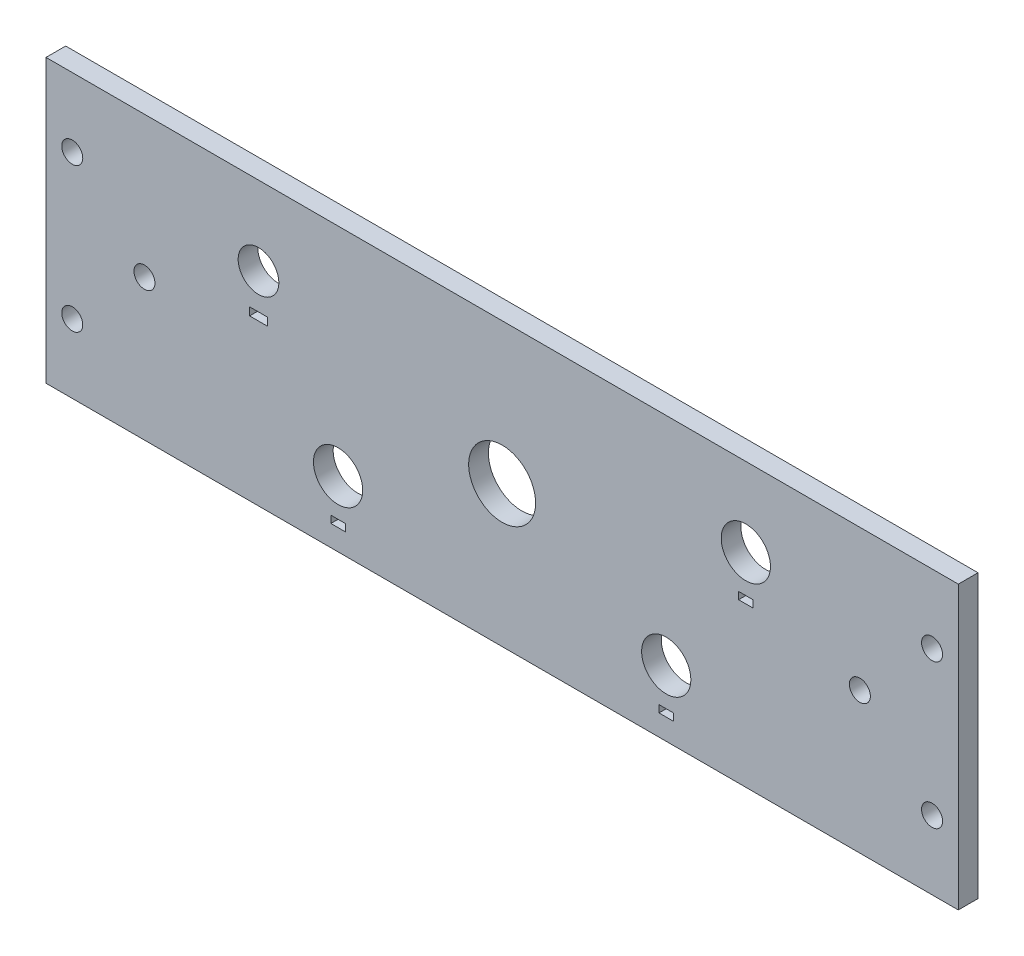
SolidWorks part; units mm, degrees
ref_plane "Front Plane" through (0, 0, 0) normal (0, 0, 1) x (1, 0, 0)
ref_plane "Top Plane" through (0, 0, 0) normal (0, 1, 0) x (1, 0, 0)
ref_plane "Right Plane" through (0, 0, 0) normal (1, 0, 0) x (0, 0, -1)
sketch "Sketch1" plane through (0, 0, 0) normal (0, 0, 1) x (1, 0, 0)
  line L0 (44.5, 10) -> (94.5, 10) construction
  line L1 (0, 0) -> (139, 0)
  line L2 (0, 0) -> (0, 43)
  line L3 (0, 43) -> (139, 43)
  line L4 (139, 0) -> (139, 43)
  line L5 (69.5, 43) -> (69.5, 0) construction
  line L12 (45.6, 3.2) -> (43.4, 4.3) construction
  line L17 (32.3756, 31) -> (32.3756, 25) construction
  line L19 (94.5, 10) -> (94.5, 0) construction
  line L20 (31.0256, 24.4) -> (33.7256, 24.4)
  line L21 (93.4, 3.2) -> (95.6, 3.2)
  line L22 (93.4, 3.2) -> (93.4, 4.3)
  line L23 (93.4, 4.3) -> (95.6, 4.3)
  line L24 (95.6, 3.2) -> (95.6, 4.3)
  line L25 (93.4, 3.2) -> (95.6, 4.3) construction
  line L26 (93.4, 4.3) -> (95.6, 3.2) construction
  line L27 (31.0256, 24.4) -> (31.0256, 25.6)
  line L28 (31.0256, 25.6) -> (33.7256, 25.6)
  line L29 (33.7256, 24.4) -> (33.7256, 25.6)
  line L30 (31.0256, 24.4) -> (33.7256, 25.6) construction
  line L31 (31.0256, 25.6) -> (33.7256, 24.4) construction
  line L35 (45.6, 4.3) -> (43.4, 3.2) construction
  line L36 (45.6, 3.2) -> (45.6, 4.3)
  line L37 (45.6, 3.2) -> (43.4, 3.2)
  line L38 (43.4, 3.2) -> (43.4, 4.3)
  line L39 (45.6, 4.3) -> (43.4, 4.3)
  line L42 (44.5, 10) -> (26.3084, 41.5087) construction
  line L45 (106.6244, 31) -> (106.6244, -29.6373) construction
  line L46 (105.5244, 24.2) -> (107.7244, 24.2)
  line L47 (105.5244, 24.2) -> (105.5244, 25.3)
  line L48 (105.5244, 25.3) -> (107.7244, 25.3)
  line L49 (107.7244, 24.2) -> (107.7244, 25.3)
  line L50 (105.5244, 24.2) -> (107.7244, 25.3) construction
  line L51 (105.5244, 25.3) -> (107.7244, 24.2) construction
  line L52 (94.5, 10) -> (106.6244, 31) construction
  circle A0 centre (32.3756, 31) radius 3.1
  circle A2 centre (94.5, 10) radius 3.75
  circle A4 centre (4, 32.5) radius 1.6
  circle A5 centre (135, 32.5) radius 1.6
  circle A6 centre (135, 10.5) radius 1.6
  circle A7 centre (4, 10.5) radius 1.6
  circle A8 centre (69.5, 21.5) radius 5.1
  circle A9 centre (15, 21.5) radius 1.6
  circle A11 centre (124, 21.5) radius 1.6
  circle A13 centre (44.5, 10) radius 3.75
  circle A15 centre (106.6244, 31) radius 3.75
  point P8 (0, 21.5)
  point P13 (69.5, 10)
  point P36 (32.3756, 25)
  point P41 (94.5, 3.75)
  point P53 (106.6244, 24.75)
  dimension "D3" = 6.2
  dimension "D4" = 7.5
  dimension "D5" = 60
  dimension "D8" = 3.2
  dimension "D24" = 7.5
  dimension "D25" = 21.5
  dimension "D29" = 2.2
  dimension "D19" = 3.2
  dimension "D31" = 7.5
  dimension "D34" = 10.2
  dimension "D1" = 139
  dimension "D2" = 43
  dimension "D6" = 50
  dimension "D7" = 10
  dimension "D11" = 131
  dimension "D12" = 4
  dimension "D13" = 10.5
  dimension "D14" = 22
  dimension "D15" = 10.5
  dimension "D16" = 12
  dimension "D17" = 15
  dimension "D18" = 15
  dimension "D20" = 4
  dimension "D21" = 2.2
  dimension "D22" = 1.1
  dimension "D23" = 5.7
  dimension "D26" = 2.7
  dimension "D27" = 1.2
  dimension "D28" = 6
  dimension "D30" = 1.1
  dimension "D32" = 5.7
  dimension "D33" = 60
  dimension "D9" = 2
  dimension "D10" = 2
extrude "Boss-Extrude1" add sketch "Sketch1" along normal blind 3
